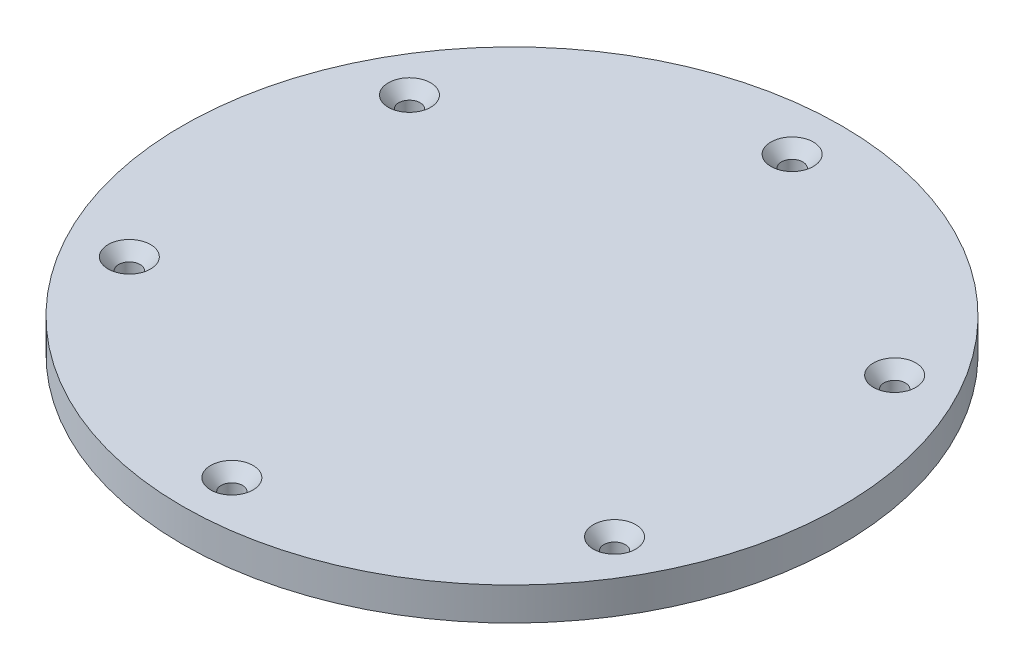
SolidWorks part; units mm, degrees
material "AISI 1020"
ref_plane "Front Plane" through (0, 0, 0) normal (0, 0, 1) x (1, 0, 0)
ref_plane "Top Plane" through (0, 0, 0) normal (0, 1, 0) x (1, 0, 0)
ref_plane "Right Plane" through (0, 0, 0) normal (1, 0, 0) x (0, 0, -1)
sketch "Sketch1" plane through (0, 0, 0) normal (0, 1, 0) x (1, 0, 0)
  circle A0 centre (0, 0) radius 100
  circle A1 centre (0, 0) radius 100 construction
extrude "Boss-Extrude1" add sketch "Sketch1" along normal blind 10
hole_wizard "CSK for 1/4 Flat Head Machine Screw1" positions "Sketch3" profile "Sketch2" countersink size "1/4" standard "ANSI Inch"
sketch "Sketch3" plane through (0, 10, 0) normal (0, 1, 0) x (1, 0, 0)
  point P0 (-73.6122, 42.5)
  point P3 (0, 85)
  point P6 (73.6122, 42.5)
  point P9 (73.6122, -42.5)
  point P12 (0, -85)
  point P15 (-73.6122, -42.5)
sketch "Sketch2" plane through (-73.6122, 10, -42.5) normal (1, 0, 0) x (0, 0, 1)
  line L0 (0, 0) -> (0, 11.9611)
  line L1 (0, 11.9611) -> (3.2639, 10)
  line L2 (3.2639, 10) -> (3.2639, 3.6524)
  line L3 (3.2639, 3.6524) -> (6.4389, 0)
  line L5 (6.4389, 0) -> (0, 0)
  line L6 (-3.2639, 3.6524) -> (-6.4389, 0) construction
  line L10 (0, 11.9611) -> (-3.2639, 10) construction
  line L11 (0, -6.35) -> (0, 107.95) construction
  dimension "Hole Dia." = 6.5278
  dimension "Hole Depth" = 10
  dimension "Near C'Sink Dia." = 12.8778
  dimension "Near C'Sink Angle" = 82
  dimension "Drill Angle" = 118
